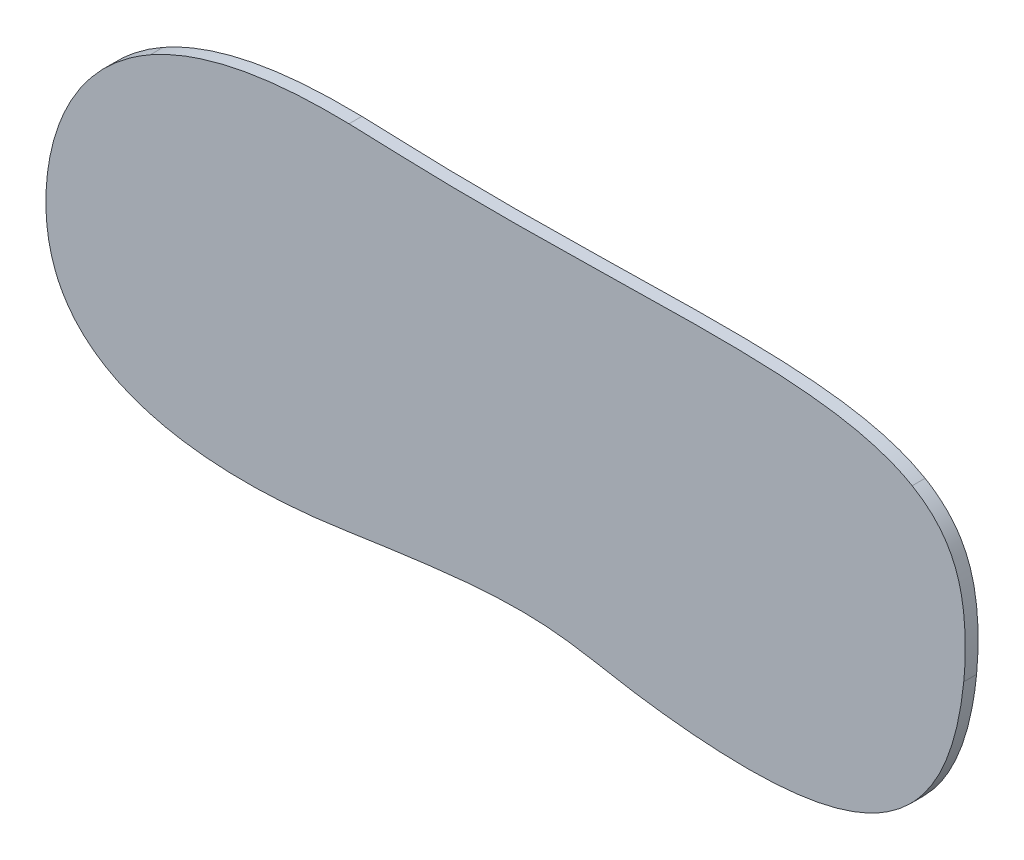
SolidWorks part; units mm, degrees
material "Natural Rubber"
ref_plane "Front Plane" through (0, 0, 0) normal (0, 0, 1) x (1, 0, 0)
ref_plane "Top Plane" through (0, 0, 0) normal (0, 1, 0) x (1, 0, 0)
ref_plane "Right Plane" through (0, 0, 0) normal (1, 0, 0) x (0, 0, -1)
sketch "Sketch1" plane through (0, 0, 0) normal (0, 0, 1) x (1, 0, 0)
  spline S18 degree 3 poles (1997.2936, -366.2193) (-320.565, -203.5196) (38.5479, -104.3193) (42.5079, 4.3603) (42.5124, 5.415) (42.4389, 7.5264) (42.361, 8.5831) (42.0987, 10.6698) (41.9154, 11.703) (41.523, 13.2301) (41.3721, 13.7353) (41.0221, 14.7362) (40.8229, 15.2316) (40.1592, 16.6696) (39.6247, 17.5742) (38.6704, 18.8419) (38.3248, 19.2516) (37.5991, 20.0223) (37.2179, 20.3853) (-6.3101, 57.87) (-246.15, -143.7457) (1170.2986, 1664.9672) knots -12.640074 -12.640074 -12.640074 -12.640074 0.125 0.125 0.25 0.25 0.375 0.375 0.5 0.5 0.5625 0.5625 0.625 0.625 0.75 0.75 0.8125 0.8125 0.875 0.875 7.648588 7.648588 7.648588 7.648588 only from (42.255, 0.1471) to (34.2428, 22.5545)
  spline S19 degree 3 poles (-477.7911, -1909.5237) (76.4744, -104.8362) (70.0044, 7.444) (30.9048, 24.163) (30.0415, 24.478) (27.4158, 25.3157) (25.6183, 25.7321) (22.8789, 26.2266) (21.9626, 26.3683) (20.1314, 26.6153) (19.2154, 26.7206) (16.4661, 26.9939) (14.6319, 27.1195) (10.9617, 27.3001) (9.1257, 27.3544) (5.4525, 27.4181) (3.6154, 27.4271) (-1.897, 27.4135) (-5.5734, 27.3508) (-12.9263, 27.2114) (-16.6029, 27.1335) (-23.9555, 27.0197) (-27.6316, 26.9833) (-34.9829, 26.9927) (-38.6582, 27.0384) (-43.2514, 27.167) (-44.1701, 27.1963) (-46.0072, 27.2624) (-46.9258, 27.2993) (-121.8124, 30.2361) (-195.8504, 26.445) (-290.5614, -1954.4041) knots -1.378976 -1.378976 -1.378976 -1.378976 0.03125 0.03125 0.0625 0.0625 0.125 0.125 0.15625 0.15625 0.1875 0.1875 0.25 0.25 0.3125 0.3125 0.375 0.375 0.5 0.5 0.625 0.625 0.75 0.75 0.875 0.875 0.90625 0.90625 0.9375 0.9375 3.453968 3.453968 3.453968 3.453968 only from (34.2428, 22.5545) to (-53.3561, 27.5089)
  spline S20 degree 3 poles (165.3426, 2009.6087) (115.2744, -110.2818) (25.6686, 32.5886) (-64.0121, 27.2179) (-66.6604, 26.9278) (-70.6014, 26.2372) (-71.9041, 25.965) (-74.4745, 25.3287) (-75.7436, 24.9643) (-144.6644, 2.0074) (-160.1005, -171.6465) (369.8767, -1923.201) knots -7.920715 -7.920715 -7.920715 -7.920715 0.25 0.25 0.5 0.5 0.625 0.625 0.75 0.75 7.510993 7.510993 7.510993 7.510993 only from (-53.3561, 27.5089) to (-84.2622, 21.3552)
  spline S21 degree 3 poles (-966.1357, 1803.6496) (395.7036, -293.1106) (-8.5143, 88.6613) (-90.3437, 16.9923) (-90.7684, 16.599) (-91.5907, 15.7939) (-91.9892, 15.3812) (-93.1466, 14.1129) (-93.8676, 13.2269) (-95.2075, 11.3737) (-95.8265, 10.4064) (-96.6768, 8.8932) (-96.9459, 8.3806) (-97.4524, 7.3467) (-97.6904, 6.8243) (-184.1809, -197.5796) (1903.8496, -1179.4768) (-2018.5077, -10.6987) knots -11.436799 -11.436799 -11.436799 -11.436799 0.25 0.25 0.3125 0.3125 0.375 0.375 0.5 0.5 0.625 0.625 0.6875 0.6875 0.75 0.75 24.897765 24.897765 24.897765 24.897765 only from (-84.2622, 21.3552) to (-99.903, -0.2825)
  spline S22 degree 3 poles (1882.3435, 229.7648) (296.244, 172.5978) (-94.6404, 88.3862) (-100.5308, -5.9597) (-100.5326, -7.3826) (-100.3678, -9.5206) (-100.2846, -10.2339) (-100.0503, -11.6621) (-99.9004, -12.368) (-99.5302, -13.7539) (-99.3096, -14.4352) (-98.7898, -15.7716) (-98.4901, -16.4279) (-97.463, -18.3469) (-96.6337, -19.5119) (-95.4247, -20.8315) (-95.1743, -21.0886) (-94.6564, -21.5894) (-94.3881, -21.8337) (-93.5643, -22.5415) (-92.9931, -22.9775) (-91.2223, -24.1917) (-89.9659, -24.8772) (-87.9921, -25.7598) (-87.32, -26.0293) (-25.3218, -48.4273) (103.4798, 121.1815) (-561.6812, -1965.3853) knots -8.0501 -8.0501 -8.0501 -8.0501 0.125 0.125 0.25 0.25 0.3125 0.3125 0.375 0.375 0.4375 0.4375 0.5 0.5 0.625 0.625 0.65625 0.65625 0.6875 0.6875 0.75 0.75 0.875 0.875 0.9375 0.9375 6.584644 6.584644 6.584644 6.584644 only from (-99.903, -0.2825) to (-84.5817, -26.9429)
  spline S23 degree 3 poles (110.8118, 1960.9671) (-178.3151, 112.8842) (-140.7662, -16.502) (-79.5023, -28.086) (-78.2138, -28.2738) (-74.3235, -28.7063) (-71.719, -28.8194) (-66.5018, -28.8019) (-63.9005, -28.6701) (-60.0129, -28.3326) (-58.719, -28.1964) (-56.7811, -27.9597) (-56.1355, -27.8753) (-6.0888, -20.9349) (40.8203, 14.9131) (264.0197, -2000.1506) knots -5.74104 -5.74104 -5.74104 -5.74104 0.125 0.125 0.25 0.25 0.5 0.5 0.75 0.75 0.875 0.875 0.9375 0.9375 5.723874 5.723874 5.723874 5.723874 only from (-84.5817, -26.9429) to (-53.5561, -27.5073)
  spline S24 degree 3 poles (-658.4461, 1868.4491) (-262.4636, -130.0926) (-157.1312, -40.1225) (-39.22, -25.5429) (-37.1661, -25.3134) (-33.0509, -24.9435) (-30.9896, -24.8028) (-26.8535, -24.6794) (-24.7932, -24.6999) (-21.724, -24.9055) (-20.7042, -25.0029) (-18.6708, -25.2516) (-17.6572, -25.4028) (-14.6219, -25.9052) (-12.6051, -26.2996) (-9.5714, -26.8156) (-8.5588, -26.9762) (148.6199, -49.4209) (347.1774, 299.1734) (244.4845, -1987.846) knots -6.808537 -6.808537 -6.808537 -6.808537 0.25 0.25 0.375 0.375 0.5 0.5 0.625 0.625 0.6875 0.6875 0.75 0.75 0.875 0.875 0.9375 0.9375 10.559628 10.559628 10.559628 10.559628 only from (-53.5561, -27.5073) to (-4.4961, -27.5095)
  spline S25 degree 3 poles (-111.8341, 1964.3032) (-168.8665, 68.3257) (-87.3246, -21.0285) (2.2151, -28.146) (3.8974, -28.2469) (7.2686, -28.3618) (8.9542, -28.3758) (12.3192, -28.2878) (13.9993, -28.1861) (16.5147, -27.9153) (17.353, -27.8052) (19.0147, -27.5402) (19.8396, -27.3851) (22.2938, -26.8431) (23.9028, -26.3797) (25.8681, -25.627) (26.2589, -25.4678) (27.0353, -25.1303) (27.4207, -24.9522) (28.5565, -24.3932) (29.2904, -23.9863) (84.2232, 10.3662) (-6.9829, 258.4638) (-928.7859, 1729.8618) knots -6.413117 -6.413117 -6.413117 -6.413117 0.125 0.125 0.25 0.25 0.375 0.375 0.5 0.5 0.5625 0.5625 0.625 0.625 0.75 0.75 0.78125 0.78125 0.8125 0.8125 0.875 0.875 5.654304 5.654304 5.654304 5.654304 only from (-4.4961, -27.5095) to (33.9433, -20.4246)
  spline S26 degree 3 poles (-1650.0839, 1054.0161) (-222.7226, 24.5404) (4.0121, -70.9093) (37.9284, -15.1613) (38.3736, -14.3274) (39.1773, -12.6294) (39.5367, -11.7637) (40.1829, -10.004) (40.4698, -9.1099) (40.9802, -7.2968) (41.2039, -6.376) (64.5911, 104.4701) (-299.766, 278.4794) (2030.4735, 6.8922) knots -8.217853 -8.217853 -8.217853 -8.217853 0.25 0.25 0.375 0.375 0.5 0.5 0.625 0.625 0.75 0.75 15.613317 15.613317 15.613317 15.613317 only from (33.9433, -20.4246) to (42.255, 0.1471)
  spline S27 degree 3 poles (42.255, 0.1471) (42.3586, 1.1994) (42.4311, 2.2525) (42.5079, 4.3603) (42.5124, 5.415) (42.4389, 7.5264) (42.361, 8.5831) (42.0987, 10.6698) (41.9154, 11.703) (41.523, 13.2301) (41.3721, 13.7353) (41.0221, 14.7362) (40.8229, 15.2316) (40.1592, 16.6696) (39.6247, 17.5742) (38.6704, 18.8419) (38.3248, 19.2516) (37.5991, 20.0223) (37.2179, 20.3853) (36.024, 21.4134) (35.1611, 22.0175) (34.2428, 22.5545) knots 0 0 0 0 0.125 0.125 0.25 0.25 0.375 0.375 0.5 0.5 0.5625 0.5625 0.625 0.625 0.75 0.75 0.8125 0.8125 0.875 0.875 1 1 1 1
  spline S28 degree 3 poles (34.2428, 22.5545) (33.4322, 23.0285) (32.6001, 23.4381) (30.9048, 24.163) (30.0415, 24.478) (27.4158, 25.3157) (25.6183, 25.7321) (22.8789, 26.2266) (21.9626, 26.3683) (20.1314, 26.6153) (19.2154, 26.7206) (16.4661, 26.9939) (14.6319, 27.1195) (10.9617, 27.3001) (9.1257, 27.3544) (5.4525, 27.4181) (3.6154, 27.4271) (-1.897, 27.4135) (-5.5734, 27.3508) (-12.9263, 27.2114) (-16.6029, 27.1335) (-23.9555, 27.0197) (-27.6316, 26.9833) (-34.9829, 26.9927) (-38.6582, 27.0384) (-43.2514, 27.167) (-44.1701, 27.1963) (-46.0072, 27.2624) (-46.9258, 27.2993) (-49.6814, 27.4074) (-51.5186, 27.4753) (-53.3561, 27.5089) knots 0 0 0 0 0.03125 0.03125 0.0625 0.0625 0.125 0.125 0.15625 0.15625 0.1875 0.1875 0.25 0.25 0.3125 0.3125 0.375 0.375 0.5 0.5 0.625 0.625 0.75 0.75 0.875 0.875 0.90625 0.90625 0.9375 0.9375 1 1 1 1
  spline S29 degree 3 poles (-53.3561, 27.5089) (-56.0222, 27.5576) (-58.6871, 27.5368) (-64.0121, 27.2179) (-66.6604, 26.9278) (-70.6014, 26.2372) (-71.9041, 25.965) (-74.4745, 25.3287) (-75.7436, 24.9643) (-79.497, 23.7141) (-81.9277, 22.674) (-84.2622, 21.3552) knots 0 0 0 0 0.25 0.25 0.5 0.5 0.625 0.625 0.75 0.75 1 1 1 1
  spline S30 degree 3 poles (-84.2622, 21.3552) (-86.2783, 20.2162) (-88.1672, 18.8985) (-90.3437, 16.9923) (-90.7684, 16.599) (-91.5907, 15.7939) (-91.9892, 15.3812) (-93.1466, 14.1129) (-93.8676, 13.2269) (-95.2075, 11.3737) (-95.8265, 10.4064) (-96.6768, 8.8932) (-96.9459, 8.3806) (-97.4524, 7.3467) (-97.6904, 6.8243) (-98.8068, 4.1859) (-99.4669, 1.9918) (-99.903, -0.2825) knots 0 0 0 0 0.25 0.25 0.3125 0.3125 0.375 0.375 0.5 0.5 0.625 0.625 0.6875 0.6875 0.75 0.75 1 1 1 1
  spline S31 degree 3 poles (-99.903, -0.2825) (-100.1746, -1.6992) (-100.3534, -3.118) (-100.5308, -5.9597) (-100.5326, -7.3826) (-100.3678, -9.5206) (-100.2846, -10.2339) (-100.0503, -11.6621) (-99.9004, -12.368) (-99.5302, -13.7539) (-99.3096, -14.4352) (-98.7898, -15.7716) (-98.4901, -16.4279) (-97.463, -18.3469) (-96.6337, -19.5119) (-95.4247, -20.8315) (-95.1743, -21.0886) (-94.6564, -21.5894) (-94.3881, -21.8337) (-93.5643, -22.5415) (-92.9931, -22.9775) (-91.2223, -24.1917) (-89.9659, -24.8772) (-87.9921, -25.7598) (-87.32, -26.0293) (-85.9627, -26.5197) (-85.2758, -26.7414) (-84.5817, -26.9429) knots 0 0 0 0 0.125 0.125 0.25 0.25 0.3125 0.3125 0.375 0.375 0.4375 0.4375 0.5 0.5 0.625 0.625 0.65625 0.65625 0.6875 0.6875 0.75 0.75 0.875 0.875 0.9375 0.9375 1 1 1 1
  spline S32 degree 3 poles (-84.5817, -26.9429) (-83.3268, -27.3073) (-82.0588, -27.6026) (-79.5023, -28.086) (-78.2138, -28.2738) (-74.3235, -28.7063) (-71.719, -28.8194) (-66.5018, -28.8019) (-63.9005, -28.6701) (-60.0129, -28.3326) (-58.719, -28.1964) (-56.7811, -27.9597) (-56.1355, -27.8753) (-54.8454, -27.6964) (-54.2007, -27.602) (-53.5561, -27.5073) knots 0 0 0 0 0.125 0.125 0.25 0.25 0.5 0.5 0.75 0.75 0.875 0.875 0.9375 0.9375 1 1 1 1
  spline S33 degree 3 poles (-53.5561, -27.5073) (-49.4656, -26.9063) (-45.3753, -26.304) (-39.22, -25.5429) (-37.1661, -25.3134) (-33.0509, -24.9435) (-30.9896, -24.8028) (-26.8535, -24.6794) (-24.7932, -24.6999) (-21.724, -24.9055) (-20.7042, -25.0029) (-18.6708, -25.2516) (-17.6572, -25.4028) (-14.6219, -25.9052) (-12.6051, -26.2996) (-9.5714, -26.8156) (-8.5588, -26.9762) (-6.5301, -27.2659) (-5.5139, -27.3951) (-4.4961, -27.5095) knots 0 0 0 0 0.25 0.25 0.375 0.375 0.5 0.5 0.625 0.625 0.6875 0.6875 0.75 0.75 0.875 0.875 0.9375 0.9375 1 1 1 1
  spline S34 degree 3 poles (-4.4961, -27.5095) (-2.8219, -27.7153) (-1.1444, -27.8789) (2.2151, -28.146) (3.8974, -28.2469) (7.2686, -28.3618) (8.9542, -28.3758) (12.3192, -28.2878) (13.9993, -28.1861) (16.5147, -27.9153) (17.353, -27.8052) (19.0147, -27.5402) (19.8396, -27.3851) (22.2938, -26.8431) (23.9028, -26.3797) (25.8681, -25.627) (26.2589, -25.4678) (27.0353, -25.1303) (27.4207, -24.9522) (28.5565, -24.3932) (29.2904, -23.9863) (31.4176, -22.656) (32.7364, -21.6226) (33.9433, -20.4246) knots 0 0 0 0 0.125 0.125 0.25 0.25 0.375 0.375 0.5 0.5 0.5625 0.5625 0.625 0.625 0.75 0.75 0.78125 0.78125 0.8125 0.8125 0.875 0.875 1 1 1 1
  spline S35 degree 3 poles (33.9433, -20.4246) (35.293, -19.085) (36.4483, -17.5942) (37.9284, -15.1613) (38.3736, -14.3274) (39.1773, -12.6294) (39.5367, -11.7637) (40.1829, -10.004) (40.4698, -9.1099) (40.9802, -7.2968) (41.2039, -6.376) (41.789, -3.6027) (42.0695, -1.7357) (42.255, 0.1471) knots 0 0 0 0 0.25 0.25 0.375 0.375 0.5 0.5 0.625 0.625 0.75 0.75 1 1 1 1
  dimension "D1" = 0.5
extrude "Boss-Extrude1" add sketch "Sketch1" along normal blind 2
